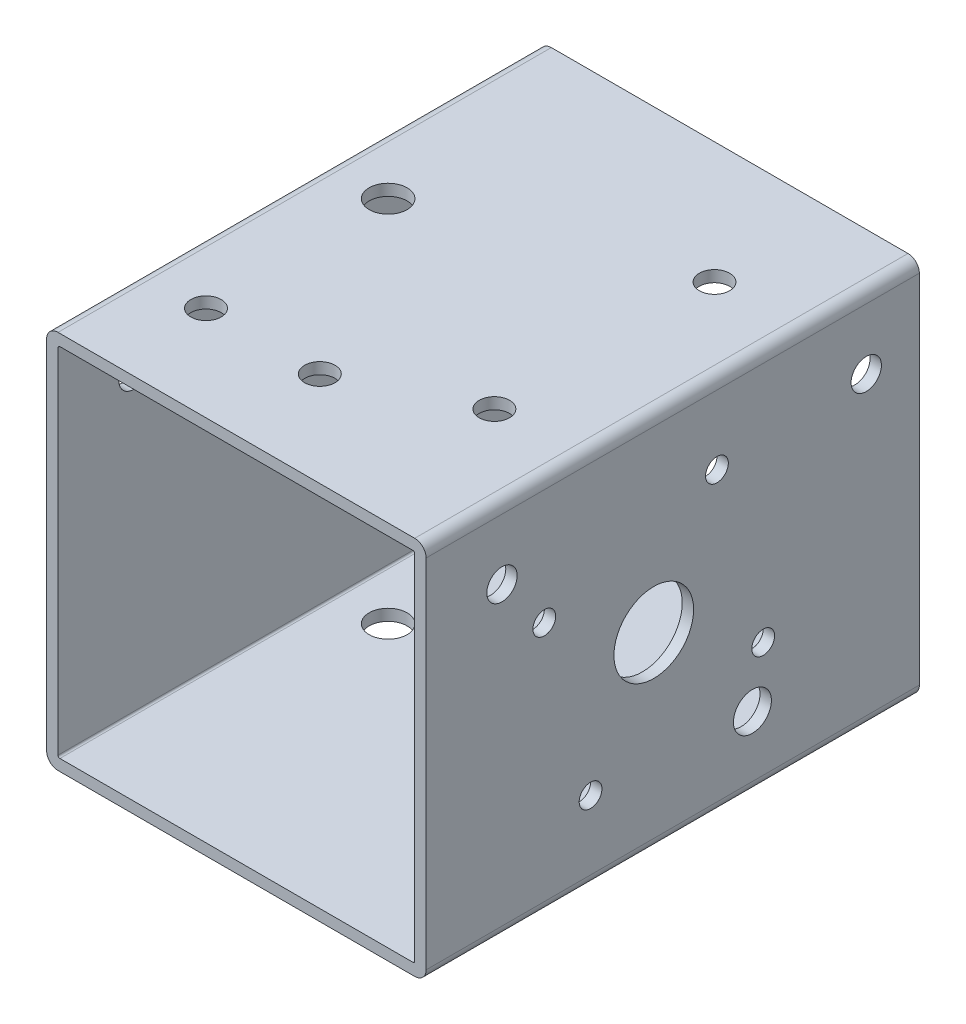
SolidWorks part; units mm, degrees
ref_plane "Front Plane" through (0, 0, 0) normal (0, 0, 1) x (1, 0, 0)
ref_plane "Top Plane" through (0, 0, 0) normal (0, 1, 0) x (1, 0, 0)
ref_plane "Right Plane" through (0, 0, 0) normal (1, 0, 0) x (0, 0, -1)
sketch "Sketch1" plane through (0, 0, 0) normal (0, 0, 1) x (1, 0, 0)
  line L1 (-50, 50) -> (50, 50)
  line L2 (-50, 50) -> (-50, -50)
  line L3 (-50, -50) -> (50, -50)
  line L4 (50, 50) -> (50, -50)
  line L5 (-50, 50) -> (50, -50) construction
  line L6 (-50, -50) -> (50, 50) construction
  point P0 (0, 0)
  dimension "D1" = 100
  dimension "D2" = 100
extrude "Extrude-Thin1" add sketch "Sketch1" along normal blind 130 thin
fillet "Fillet1" radius 0.5 4 edges at (-47, -47, 65) (-47, 47, 65) (47, 47, 65) (47, -47, 65)
fillet "Fillet2" radius 3 4 edges at (50, -50, 65) (-50, -50, 65) (50, 50, 65) (-50, 50, 65)
sketch "Holes - top" plane through (0, 0, 0) normal (0, 1, 0) x (1, 0, 0)
  line L0 (-3, 0) -> (-3, -130) construction
  line L1 (47, -130) -> (-47, -130) construction
  line L2 (-23, 0) -> (-23, -130) construction
  line L3 (47, 0) -> (-47, 0) construction
  line L4 (17, 0) -> (17, -130) construction
  circle A0 centre (-34, -56) radius 11 construction
  circle A1 centre (28, -90) radius 11 construction
  circle A2 centre (28, -32) radius 11 construction
  dimension "D4" = 22
  dimension "D1" = 40
  dimension "D2" = 40
  dimension "D3" = 32
  dimension "D5" = 56
  dimension "D6" = 3
hole_wizard "Ø8.0 (8) Diameter Hole2" positions "Sketch6" profile "Sketch5" hole size "Ø8.0" standard "ANSI Metric" end condition through all
sketch "Sketch6" plane through (0, 50, 0) normal (0, 1, 0) x (1, 0, 0)
  point P0 (28, -32)
  point P6 (28, -90)
sketch "Sketch5" plane through (28, 50, 32) normal (1, 0, 0) x (0, 0, 1)
  line L0 (0, 0) -> (0, 100)
  line L1 (0, 100) -> (4, 100)
  line L2 (4, 100) -> (4, 0)
  line L5 (4, 0) -> (0, 0)
  line L11 (0, -6.35) -> (0, 107.95) construction
  dimension "Thru Hole Dia." = 8
  dimension "Thru Hole Depth" = 100
sketch "Holes - side" plane through (0, 0, 0) normal (1, 0, 0) x (0, 0, -1)
  line L0 (0, 0) -> (-130, 0) construction
  line L1 (-130, -47) -> (-130, 47) construction
  line L2 (-130, 20) -> (0, 20) construction
  line L3 (0, -47) -> (0, 47) construction
  line L4 (-130, -20) -> (0, -20) construction
  circle A0 centre (-110, 31) radius 11 construction
  circle A1 centre (-14, 31) radius 11 construction
  circle A2 centre (-44, -31) radius 11 construction
  dimension "D1" = 40
  dimension "D2" = 22
  dimension "D3" = 20
  dimension "D4" = 14
  dimension "D5" = 44
hole_wizard "Ø8.0 (8) Diameter Hole3" positions "Sketch9" profile "Sketch8" hole size "Ø8.0" standard "ANSI Metric" end condition through all
sketch "Sketch9" plane through (50, 0, 0) normal (1, 0, 0) x (0, 0, -1)
  point P0 (-14, 31)
  point P3 (-110, 31)
sketch "Sketch8" plane through (50, 31, 14) normal (0, 1, 0) x (0, 0, -1)
  line L0 (0, 0) -> (0, 100)
  line L1 (0, 100) -> (4, 100)
  line L2 (4, 100) -> (4, 0)
  line L5 (4, 0) -> (0, 0)
  line L11 (0, -6.35) -> (0, 107.95) construction
  dimension "Thru Hole Dia." = 8
  dimension "Thru Hole Depth" = 100
hole_wizard "Ø10.0 (10) Diameter Hole1" positions "Sketch12" profile "Sketch11" hole size "Ø10.0" standard "ANSI Metric" end condition through all
sketch "Sketch12" plane through (0, 50, 0) normal (0, 1, 0) x (1, 0, 0)
  point P0 (-34, -56)
sketch "Sketch11" plane through (-34, 50, 56) normal (1, 0, 0) x (0, 0, 1)
  line L0 (0, 0) -> (0, 100)
  line L1 (0, 100) -> (5, 100)
  line L2 (5, 100) -> (5, 0)
  line L5 (5, 0) -> (0, 0)
  line L11 (0, -6.35) -> (0, 107.95) construction
  dimension "Thru Hole Dia." = 10
  dimension "Thru Hole Depth" = 100
hole_wizard "Ø10.0 (10) Diameter Hole2" positions "Sketch14" profile "Sketch13" hole size "Ø10.0" standard "ANSI Metric" end condition through all
sketch "Sketch14" plane through (50, 0, 0) normal (1, 0, 0) x (0, 0, -1)
  point P0 (-44, -31)
sketch "Sketch13" plane through (50, -31, 44) normal (0, 1, 0) x (0, 0, -1)
  line L0 (0, 0) -> (0, 100)
  line L1 (0, 100) -> (5, 100)
  line L2 (5, 100) -> (5, 0)
  line L5 (5, 0) -> (0, 0)
  line L11 (0, -6.35) -> (0, 107.95) construction
  dimension "Thru Hole Dia." = 10
  dimension "Thru Hole Depth" = 100
hole_wizard "Ø6.0 (6) Diameter Hole2" positions "Sketch18" profile "Sketch17" hole size "Ø6.0" standard "ANSI Metric"
sketch "Sketch18" plane through (-50, 0, 0) normal (-1, 0, 0) x (0, 0, 1)
  line L0 (56, 35) -> (56, -15) construction
  point P0 (56, -15)
  point P2 (56, 35)
  dimension "D1" = 56
  dimension "D2" = 35
  dimension "D3" = 15
sketch "Sketch17" plane through (-50, -15, 56) normal (0, 1, 0) x (0, 0, 1)
  line L0 (0, 0) -> (0, 3)
  line L1 (0, 3) -> (3, 3)
  line L2 (3, 3) -> (3, 0)
  line L5 (3, 0) -> (0, 0)
  line L11 (0, -6.35) -> (0, 107.95) construction
  dimension "Thru Hole Dia." = 6
  dimension "Thru Hole Depth" = 3
hole_wizard "Ø6.0 (6) Diameter Hole3" positions "Sketch21" profile "Sketch20" hole size "Ø6.0" standard "ANSI Metric"
sketch "Sketch21" plane through (0, -50, 0) normal (0, -1, 0) x (-1, 0, 0)
  line L0 (20, -44) -> (-35, -44) construction
  point P0 (20, -44)
  point P2 (-35, -44)
  dimension "D1" = 44
  dimension "D2" = 35
  dimension "D3" = 20
sketch "Sketch20" plane through (-20, -50, 44) normal (1, 0, 0) x (0, 0, -1)
  line L0 (0, 0) -> (0, 3)
  line L1 (0, 3) -> (3, 3)
  line L2 (3, 3) -> (3, 0)
  line L5 (3, 0) -> (0, 0)
  line L11 (0, -6.35) -> (0, 107.95) construction
  dimension "Thru Hole Dia." = 6
  dimension "Thru Hole Depth" = 3
sketch "Holes - Nema 23 motor" plane through (0, 0, 0) normal (1, 0, 0) x (0, 0, -1)
  line L0 (-98.8427, 16.6524) -> (-53.3476, 28.8427) construction
  line L1 (-98.8427, 16.6524) -> (-86.6524, -28.8427) construction
  line L2 (-53.3476, 28.8427) -> (-41.1573, -16.6524) construction
  line L3 (-86.6524, -28.8427) -> (-41.1573, -16.6524) construction
  line L4 (-98.8427, 16.6524) -> (-41.1573, -16.6524) construction
  line L5 (-53.3476, 28.8427) -> (-86.6524, -28.8427) construction
  line L6 (0, 0) -> (-130, 0) construction
  point P1 (-70, 0)
  dimension "D1" = 70
  dimension "D2" = 47.1
  dimension "D3" = 47.1
  dimension "D4" = 15
hole_wizard "Ø21.0 (21) Diameter Hole1" positions "Sketch24" profile "Sketch23" hole size "Ø21.0" standard "ANSI Metric"
sketch "Sketch24" plane through (50, 0, 0) normal (1, 0, 0) x (0, 0, -1)
  point P0 (-70, 0)
sketch "Sketch23" plane through (50, 0, 70) normal (0, 1, 0) x (0, 0, -1)
  line L0 (0, 0) -> (0, 3)
  line L1 (0, 3) -> (10.5, 3)
  line L2 (10.5, 3) -> (10.5, 0)
  line L5 (10.5, 0) -> (0, 0)
  line L11 (0, -6.35) -> (0, 107.95) construction
  dimension "Thru Hole Dia." = 21
  dimension "Thru Hole Depth" = 3
hole_wizard "Ø6.0 (6) Diameter Hole1" positions "Sketch26" profile "Sketch25" hole size "Ø6.0" standard "ANSI Metric"
sketch "Sketch26" plane through (50, 0, 0) normal (1, 0, 0) x (0, 0, -1)
  point P0 (-41.1573, -16.6524)
  point P3 (-53.3476, 28.8427)
  point P6 (-98.8427, 16.6524)
  point P9 (-86.6524, -28.8427)
sketch "Sketch25" plane through (50, -16.6524, 41.1573) normal (0, 1, 0) x (0, 0, -1)
  line L0 (0, 0) -> (0, 3)
  line L1 (0, 3) -> (3, 3)
  line L2 (3, 3) -> (3, 0)
  line L5 (3, 0) -> (0, 0)
  line L11 (0, -6.35) -> (0, 107.95) construction
  dimension "Thru Hole Dia." = 6
  dimension "Thru Hole Depth" = 3
hole_wizard "Ø8.0 (8) Diameter Hole4" positions "Sketch29" profile "Sketch28" hole size "Ø8.0" standard "ANSI Metric"
sketch "Sketch29" plane through (0, 50, 0) normal (0, 1, 0) x (1, 0, 0)
  line L0 (-3, 0) -> (-3, -130) construction
  point P0 (-3, -105)
  dimension "D1" = 15
sketch "Sketch28" plane through (-3, 50, 105) normal (1, 0, 0) x (0, 0, 1)
  line L0 (0, 0) -> (0, 3)
  line L1 (0, 3) -> (4, 3)
  line L2 (4, 3) -> (4, 0)
  line L5 (4, 0) -> (0, 0)
  line L11 (0, -6.35) -> (0, 107.95) construction
  dimension "Thru Hole Dia." = 8
  dimension "Thru Hole Depth" = 3
sketch "Sketch32" plane through (50, 0, 0) normal (1, 0, 0) x (0, 0, -1)
  line L1 (0, -47) -> (0, 47) construction
  line L2 (-65, 69.5535) -> (-65, -72.7704) construction
  line L3 (-130, -47) -> (-130, 47) construction
  line L4 (-130, 50) -> (0, 50) construction
  circle A0 centre (-5, 13) radius 2
  circle A1 centre (-5, 4) radius 2
  circle A2 centre (-125, 4) radius 2
  circle A3 centre (-125, 13) radius 2
  dimension "D1" = 46
  dimension "D2" = 9
  dimension "D3" = 4
  dimension "D5" = 5
  dimension "D4" = 0
  dimension "D6" = 65
sketch "Sketch33" plane through (0, 50, 0) normal (0, 1, 0) x (1, 0, 0)
  line L0 (47, -130) -> (-47, -130) construction
  circle A0 centre (-33, -105) radius 4
  circle A2 centre (-3, -105) radius 4 construction
  dimension "D3" = 8
  dimension "D1" = 25
  dimension "D2" = 30
extrude "Cut-Extrude1" cut sketch "Sketch33" against normal blind 10
equation "\"L\"= 130"
equation "\"D1@Extrude-Thin1\"=\"L\""
equation "\"d-bearing\"= 22'diameter of bearing"
equation "\"D4@Holes - top\"=\"d-bearing\""
equation "\"D2@Holes - side\"=\"d-bearing\""
